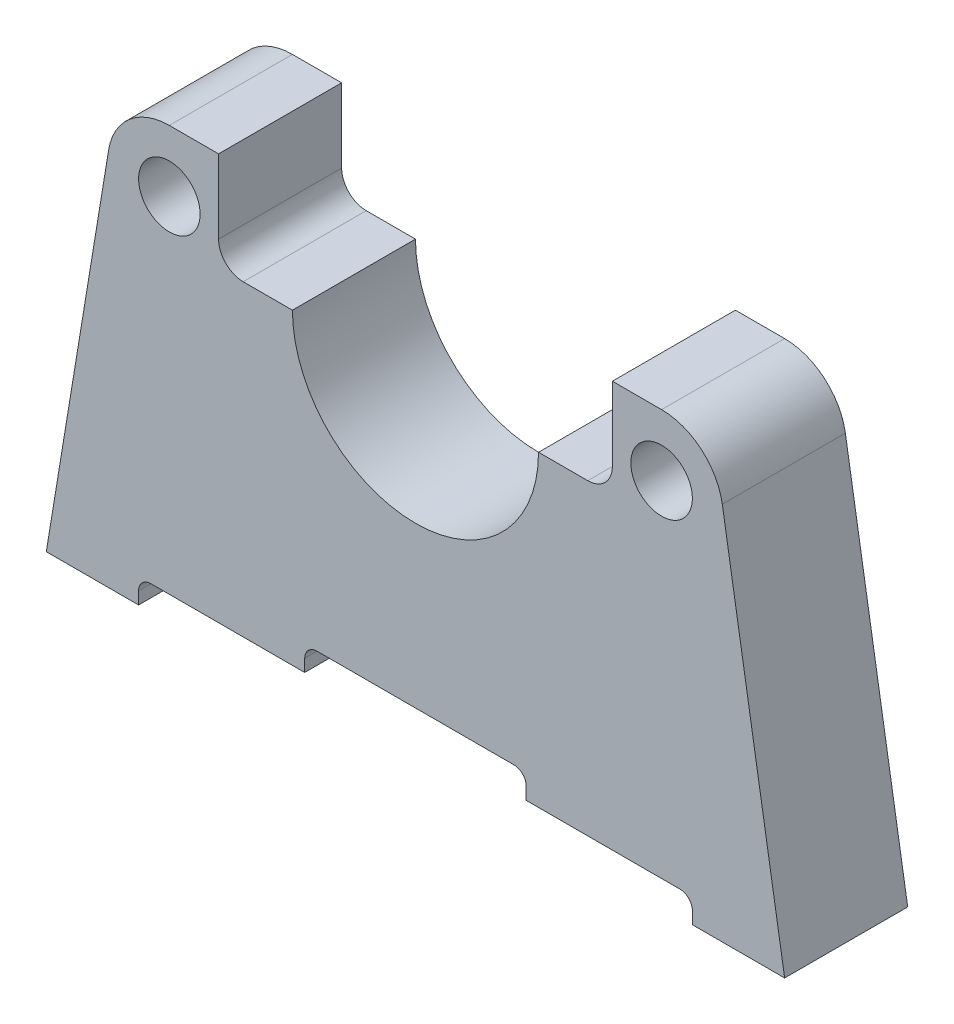
SolidWorks part; units mm, degrees
ref_plane "Front Plane" through (0, 0, 0) normal (0, 0, 1) x (1, 0, 0)
ref_plane "Top Plane" through (0, 0, 0) normal (0, 1, 0) x (1, 0, 0)
ref_plane "Right Plane" through (0, 0, 0) normal (1, 0, 0) x (0, 0, -1)
sketch "Sketch1" plane through (0, 0, 0) normal (0, 0, 1) x (1, 0, 0)
  line L0 (0, 0) -> (102556.7584, 0) construction
  line L1 (0, 0) -> (0, 102556.7584) construction
  line L2 (-30, 0) -> (-22.5, 0)
  line L3 (-22.5, 0) -> (-22.5, 1)
  line L4 (-21.5, 2) -> (-9, 2)
  line L5 (-9, 2) -> (-9, 3)
  line L6 (-8, 4) -> (8, 4)
  line L7 (-30, 0) -> (-24.9337, 30.8112)
  line L8 (-20, 35) -> (-16, 35)
  line L9 (-16, 35) -> (-16, 29)
  line L10 (-14, 27) -> (-10, 27)
  line L11 (14, 27) -> (10, 27)
  line L12 (16, 35) -> (16, 29)
  line L13 (20, 35) -> (16, 35)
  line L14 (30, 0) -> (24.9337, 30.8112)
  line L15 (9, 2) -> (9, 3)
  line L16 (21.5, 2) -> (9, 2)
  line L17 (22.5, 0) -> (22.5, 1)
  line L18 (30, 0) -> (22.5, 0)
  arc A0 (-10, 27) -> (10, 27) centre (0, 27) ccw
  arc A1 (21.5, 2) -> (22.5, 1) centre (21.5, 1) cw
  arc A2 (9, 3) -> (8, 4) centre (8, 3) ccw
  arc A3 (-9, 3) -> (-8, 4) centre (-8, 3) cw
  arc A4 (-22.5, 1) -> (-21.5, 2) centre (-21.5, 1) cw
  arc A5 (20, 35) -> (24.9337, 30.8112) centre (20, 30) cw
  arc A6 (-24.9337, 30.8112) -> (-20, 35) centre (-20, 30) cw
  circle A7 centre (-20, 30) radius 2.5
  circle A8 centre (20, 30) radius 2.5
  arc A9 (14, 27) -> (16, 29) centre (14, 29) ccw
  arc A10 (-16, 29) -> (-14, 27) centre (-14, 29) ccw
  point P18 (0, 4)
  point P27 (16, 27)
  point P31 (22.5, 2)
  point P34 (9, 4)
  point P37 (-9, 4)
  point P40 (-22.5, 2)
  point P44 (24.245, 35)
  point P47 (-24.245, 35)
  point P51 (-16, 27)
  point P52 (0, 23.7508)
  point P53 (0, 0)
  point P54 (0, 0)
  dimension "D1" = 60
  dimension "D4" = 1
  dimension "D7" = 5
  dimension "D8" = 5
  dimension "D9" = 40
  dimension "D11" = 2
  dimension "D13" = 10
  dimension "D2" = 45
  dimension "D3" = 18
  dimension "D5" = 2
  dimension "D6" = 4
  dimension "D10" = 32
  dimension "D12" = 30
  dimension "D14" = 27
extrude "Boss-Extrude1" add sketch "Sketch1" along normal blind 10
